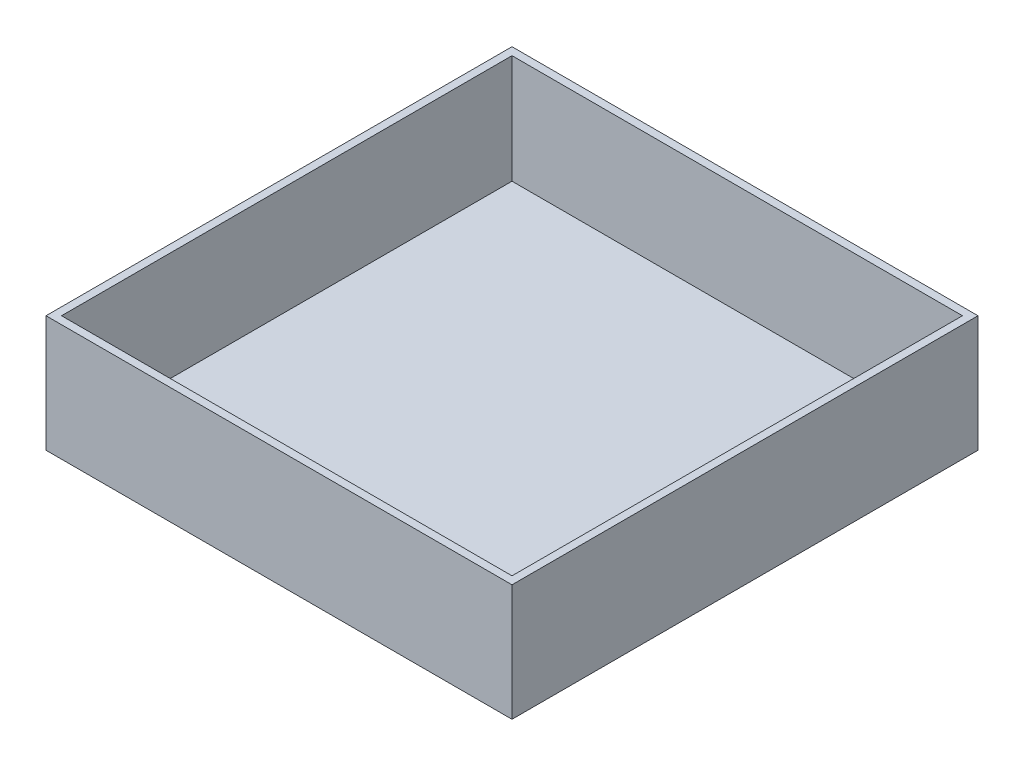
SolidWorks part; units mm, degrees
ref_plane "Front Plane" through (0, 0, 0) normal (0, 0, 1) x (1, 0, 0)
ref_plane "Top Plane" through (0, 0, 0) normal (0, 1, 0) x (1, 0, 0)
ref_plane "Right Plane" through (0, 0, 0) normal (1, 0, 0) x (0, 0, -1)
sketch "Sketch1" plane through (0, 0, 0) normal (0, 1, 0) x (1, 0, 0)
  line L1 (0, 0) -> (60, 0)
  line L2 (0, 0) -> (0, 60)
  line L3 (0, 60) -> (60, 60)
  line L4 (60, 0) -> (60, 60)
  dimension "D1" = 60
  dimension "D2" = 60
extrude "Boss-Extrude1" add sketch "Sketch1" along normal blind 1
sketch "Sketch2" plane through (0, 1, 0) normal (0, 1, 0) x (1, 0, 0)
  line L8 (0, 60) -> (0, 0)
  line L9 (0, 0) -> (60, 0)
  line L10 (60, 0) -> (60, 60)
  line L11 (60, 60) -> (0, 60)
  line L12 (0, 60) -> (0, 0)
  line L13 (0, 0) -> (60, 0)
  line L14 (60, 0) -> (60, 60)
  line L15 (60, 60) -> (0, 60)
  line L20 (1, 59) -> (1, 1)
  line L21 (1, 1) -> (59, 1)
  line L22 (59, 1) -> (59, 59)
  line L23 (59, 59) -> (1, 59)
  line L24 (1, 59) -> (1, 1)
  line L25 (1, 1) -> (59, 1)
  line L26 (59, 1) -> (59, 59)
  line L27 (59, 59) -> (1, 59)
  dimension "D1" = 0
  dimension "D2" = 1
extrude "Boss-Extrude2" add sketch "Sketch2" along normal blind 14
